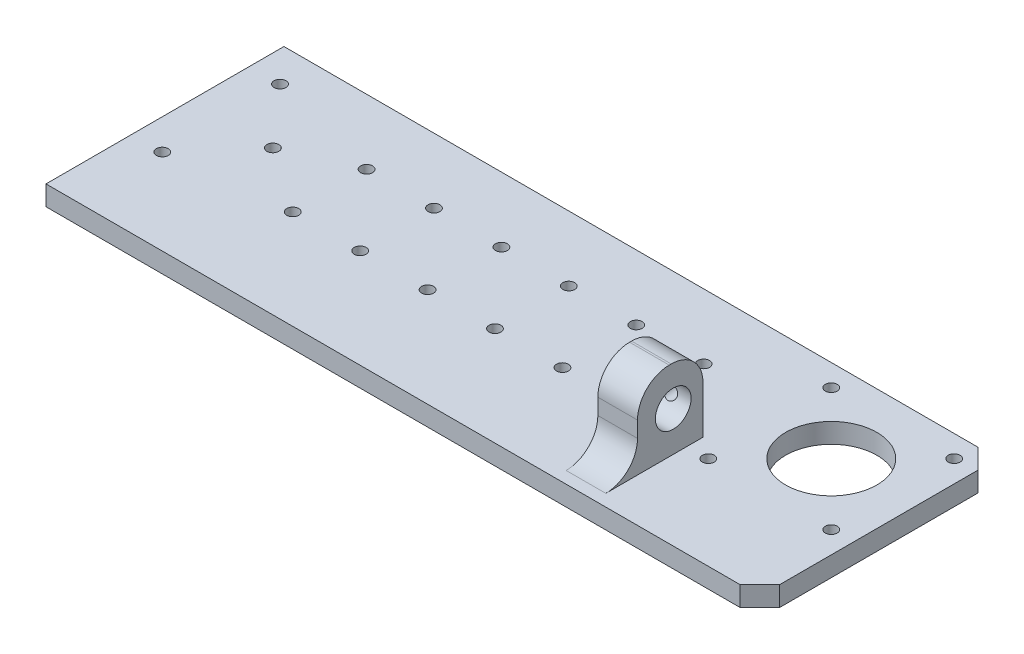
SolidWorks part; units mm, degrees
ref_plane "정면" through (0, 0, 0) normal (0, 0, 1) x (1, 0, 0)
ref_plane "윗면" through (0, 0, 0) normal (0, 1, 0) x (1, 0, 0)
ref_plane "우측면" through (0, 0, 0) normal (1, 0, 0) x (0, 0, -1)
sketch "스케치1" plane through (0, 0, 0) normal (0, 1, 0) x (1, 0, 0)
  line L0 (-53.3677, 28.2576) -> (-53.3677, -31.7424)
  line L1 (-53.3677, -31.7424) -> (126.6323, -31.7424)
  line L2 (126.6323, -31.7424) -> (126.6323, 28.2576)
  line L3 (126.6323, 28.2576) -> (-53.3677, 28.2576)
  circle A0 centre (105.6323, 7.2576) radius 11
  circle A2 centre (90.1323, 22.7576) radius 1.5
  circle A3 centre (121.1323, 22.7576) radius 1.5
  circle A4 centre (90.1323, -8.2424) radius 1.5
  circle A5 centre (121.1323, -8.2424) radius 1.5
  circle A6 centre (-32.6178, 4.7126) radius 1.5
  circle A7 centre (-45.6544, 19.5487) radius 1.5
  circle A8 centre (-45.6544, -10.1235) radius 1.5
  dimension "D4" = 31
  dimension "D1" = 180
  dimension "D3" = 60
  dimension "D5" = 31
extrude "보스-돌출3" add sketch "스케치1" along normal blind 5
sketch "스케치2" plane through (0, 5, 0) normal (0, 1, 0) x (1, 0, 0)
  line L2 (84.7825, 18.2576) -> (74.7825, 18.2576)
  line L3 (74.7825, 18.2576) -> (74.7825, -1.7424)
  line L4 (74.7825, -1.7424) -> (84.7825, -1.7424)
  line L5 (84.7825, -1.7424) -> (84.7825, 18.2576)
extrude "보스-돌출4" add sketch "스케치2" along normal blind 20
sketch "스케치4" plane through (74.7825, 0, 0) normal (-1, 0, 0) x (0, 0, 1)
  line L0 (1.7424, 25) -> (-8.2576, 25)
  line L1 (-18.2576, 25) -> (1.7424, 25) construction
  line L2 (-8.2576, 25) -> (-8.2576, 15)
  circle A0 centre (-8.2576, 15) radius 4
extrude "컷-돌출1" cut sketch "스케치4" against normal blind 20
sketch "스케치7" plane through (84.7825, 0, 0) normal (1, 0, 0) x (0, 0, -1)
  line L0 (18.2576, 25) -> (15.2576, 25)
  line L1 (-1.7424, 25) -> (18.2576, 25) construction
  line L2 (15.2576, 25) -> (15.2576, 5)
  line L3 (-1.7424, 5) -> (18.2576, 5) construction
  line L4 (15.2576, 5) -> (18.2576, 5)
  line L5 (18.2576, 5) -> (18.2576, 25)
  line L6 (-1.7424, 25) -> (1.2576, 25)
  line L7 (1.2576, 25) -> (1.2576, 5)
  line L8 (1.2576, 5) -> (-1.7424, 5)
  line L9 (-1.7424, 5) -> (-1.7424, 25)
  dimension "D1" = 3
  dimension "D2" = 3
sketch "스케치8" plane through (84.7825, 0, 0) normal (1, 0, 0) x (0, 0, -1)
  line L1 (15.2576, 25) -> (18.2576, 25)
  line L2 (15.2576, 25) -> (15.2576, 5)
  line L3 (15.2576, 5) -> (18.2576, 5)
  line L4 (18.2576, 25) -> (18.2576, 5)
  line L5 (1.2576, 25) -> (-1.7424, 25)
  line L6 (1.2576, 25) -> (1.2576, 5)
  line L7 (1.2576, 5) -> (-1.7424, 5)
  line L8 (-1.7424, 25) -> (-1.7424, 5)
extrude "컷-돌출4" cut sketch "스케치8" against normal blind 10
sketch "스케치9" plane through (84.7825, 0, 0) normal (1, 0, 0) x (0, 0, -1)
  line L0 (8.2576, 15) -> (1.7576, 15)
  line L1 (1.7576, 15) -> (1.7576, 5)
  line L2 (1.2576, 25) -> (15.2576, 25)
  line L3 (1.2576, 25) -> (1.2576, 5)
  line L4 (1.2576, 5) -> (15.2576, 5)
  line L5 (15.2576, 25) -> (15.2576, 5)
  line L6 (1.7576, 5) -> (1.7576, 25)
  line L8 (1.7576, 25) -> (-12.2424, 25)
  line L9 (1.7576, 25) -> (1.7576, 5)
  line L10 (1.7576, 5) -> (-12.2424, 5)
  line L11 (-12.2424, 25) -> (-12.2424, 5)
  circle A0 centre (-5.2424, 15) radius 4
  dimension "D3" = 8
  dimension "D1" = 14
  dimension "D2" = 6.5
  dimension "D4" = 7
sketch "스케치10" plane through (84.7825, 0, 0) normal (1, 0, 0) x (0, 0, -1)
  line L1 (-12.2424, 25) -> (1.7576, 25)
  line L2 (-12.2424, 25) -> (-12.2424, 5)
  line L3 (-12.2424, 5) -> (1.7576, 5)
  line L4 (1.7576, 25) -> (1.7576, 5)
extrude "보스-돌출5" add sketch "스케치10" against normal blind 10
extrude "컷-돌출5" cut sketch "스케치9" against normal blind 10 contours A0
sketch "스케치11" plane through (84.7825, 0, 0) normal (1, 0, 0) x (0, 0, -1)
  line L1 (-12.2424, 5) -> (15.2576, 5) construction
  line L3 (1.7576, 5) -> (15.2576, 5)
  line L4 (1.7576, 5) -> (1.7576, 25)
  line L5 (1.7576, 25) -> (15.2576, 25)
  line L6 (15.2576, 5) -> (15.2576, 25)
sketch "스케치12" plane through (84.7825, 0, 0) normal (1, 0, 0) x (0, 0, -1)
  line L1 (1.7576, 25) -> (15.2576, 25)
  line L2 (1.7576, 25) -> (1.7576, 5)
  line L3 (1.7576, 5) -> (15.2576, 5)
  line L4 (15.2576, 25) -> (15.2576, 5)
extrude "컷-돌출6" cut sketch "스케치12" against normal blind 10
sketch "스케치14" plane through (0, 5, 0) normal (0, 1, 0) x (1, 0, 0)
  line L0 (105.6323, 7.2576) -> (105.6323, 0.7576)
  line L1 (84.7825, 1.7576) -> (105.6323, 1.7576)
  dimension "D1" = 6.5
sketch "스케치15" plane through (84.7825, 0, 0) normal (1, 0, 0) x (0, 0, -1)
  line L0 (-12.2424, 5) -> (1.7576, 5) construction
  line L1 (1.7576, 25) -> (0.7576, 25)
  line L2 (1.7576, 25) -> (1.7576, 5)
  line L3 (1.7576, 5) -> (0.7576, 5)
  line L4 (0.7576, 25) -> (0.7576, 5)
  dimension "D1" = 1
extrude "컷-돌출7" cut sketch "스케치15" against normal blind 10
fillet "필렛5" radius 5 2 edges at (79.7825, 25, -0.7576) (79.7825, 25, 12.2424)
sketch "스케치16" plane through (0, 5, 0) normal (0, 1, 0) x (1, 0, 0)
  line L0 (105.6323, 7.2576) -> (105.6323, 0.7576)
sketch "스케치17" plane through (0, 5, 0) normal (0, 1, 0) x (1, 0, 0)
  line L0 (105.6323, 7.2576) -> (105.6323, -5.7424)
  line L1 (105.6323, -5.7424) -> (84.7825, -5.7424)
  line L2 (84.7825, -12.2424) -> (84.7825, 0.7576) construction
  line L3 (74.7825, 0.7576) -> (74.7825, -12.2424) construction
  line L4 (84.7825, -5.7424) -> (74.7825, -5.7424)
  line L5 (84.7825, -5.7424) -> (84.7825, 3.2576)
  line L6 (84.7825, 3.2576) -> (74.7825, 3.2576)
  line L7 (74.7825, -5.7424) -> (74.7825, 3.2576)
  line L9 (84.7825, -5.7424) -> (74.7825, -5.7424)
  line L10 (84.7825, -5.7424) -> (84.7825, -14.7424)
  line L11 (84.7825, -14.7424) -> (74.7825, -14.7424)
  line L12 (74.7825, -5.7424) -> (74.7825, -14.7424)
  dimension "D1" = 9
  dimension "D2" = 9
sketch "스케치20" plane through (74.7825, 0, 0) normal (-1, 0, 0) x (0, 0, 1)
  line L1 (-3.2576, 5) -> (-1.0985, 5)
  line L2 (-3.2576, 5) -> (-3.2576, 27.106)
  line L3 (-3.2576, 27.106) -> (-1.0985, 27.106)
  line L4 (-1.0985, 5) -> (-1.0985, 27.106)
sketch "스케치21" plane through (0, 5, 0) normal (0, 1, 0) x (1, 0, 0)
  line L1 (84.7825, -14.7424) -> (74.7825, -14.7424)
  line L2 (84.7825, -14.7424) -> (84.7825, 3.2576)
  line L3 (84.7825, 3.2576) -> (74.7825, 3.2576)
  line L4 (74.7825, -14.7424) -> (74.7825, 3.2576)
extrude "보스-돌출6" add sketch "스케치21" along normal blind 20
sketch "스케치23" plane through (84.7825, 0, 0) normal (1, 0, 0) x (0, 0, -1)
  line L1 (-14.7424, 25) -> (3.2576, 25) construction
  circle A0 centre (-5.7424, 15) radius 4
  dimension "D1" = 10
sketch "스케치24" plane through (0, 5, 0) normal (0, 1, 0) x (1, 0, 0)
  line L0 (105.6323, 7.2576) -> (105.6323, 0.7576)
sketch "스케치25" plane through (0, 5, 0) normal (0, 1, 0) x (1, 0, 0)
  line L1 (84.7825, 3.2576) -> (73.4713, 3.2576)
  line L2 (84.7825, 3.2576) -> (84.7825, 1.7576)
  line L3 (84.7825, 1.7576) -> (73.4713, 1.7576)
  line L4 (73.4713, 3.2576) -> (73.4713, 1.7576)
extrude "컷-돌출10" cut sketch "스케치25" along normal blind 20
sketch "스케치28" plane through (0, 5, 0) normal (0, 1, 0) x (1, 0, 0)
  line L1 (84.7825, 1.7576) -> (74.7825, 1.7576)
  line L2 (84.7825, 1.7576) -> (84.7825, -14.7424)
  line L3 (84.7825, -14.7424) -> (74.7825, -14.7424)
  line L4 (74.7825, 1.7576) -> (74.7825, -14.7424)
sketch "스케치31" plane through (0, 5, 0) normal (0, 1, 0) x (1, 0, 0)
  line L0 (105.6323, 7.2576) -> (105.6323, 0.7576)
sketch "스케치34" plane through (0, 0, 14.7424) normal (0, 0, 1) x (1, 0, 0)
  line L1 (74.7825, 25) -> (84.7825, 25)
  line L2 (74.7825, 25) -> (74.7825, 5)
  line L3 (74.7825, 5) -> (84.7825, 5)
  line L4 (84.7825, 25) -> (84.7825, 5)
sketch "스케치36" plane through (84.7825, 0, 0) normal (1, 0, 0) x (0, 0, -1)
  line L0 (1.7576, 25) -> (-5.7424, 25)
  line L1 (-14.7424, 25) -> (1.7576, 25) construction
  line L6 (1.7576, 5) -> (1.7576, 25)
  line L7 (1.7576, 25) -> (-14.7424, 25)
  line L8 (-14.7424, 25) -> (-14.7424, 5)
  line L9 (-14.7424, 5) -> (1.7576, 5)
  line L11 (1.7576, 25) -> (-5.7424, 25)
  dimension "D1" = 0
sketch "스케치37" plane through (0, 0, 14.7424) normal (0, 0, 1) x (1, 0, 0)
  line L1 (84.7825, 25) -> (74.7825, 25)
  line L2 (84.7825, 25) -> (84.7825, 5)
  line L3 (84.7825, 5) -> (74.7825, 5)
  line L4 (74.7825, 25) -> (74.7825, 5)
extrude "보스-돌출9" add sketch "스케치37" along normal blind 6
sketch "스케치38" plane through (0, 0, -1.7576) normal (0, 0, -1) x (-1, 0, 0)
  line L1 (-74.7825, 25) -> (-84.7825, 25)
  line L2 (-74.7825, 25) -> (-74.7825, 5)
  line L3 (-74.7825, 5) -> (-84.7825, 5)
  line L4 (-84.7825, 25) -> (-84.7825, 5)
extrude "컷-돌출12" cut sketch "스케치38" against normal blind 6
sketch "스케치39" plane through (84.7825, 0, 0) normal (1, 0, 0) x (0, 0, -1)
  line L0 (-4.2424, 25) -> (-4.2424, 5) construction
  circle A0 centre (-11.7424, 15) radius 4
  dimension "D1" = 7.5
extrude "컷-돌출13" cut sketch "스케치39" against normal through all
fillet "필렛10" radius 8 3 edges at (79.7825, 25, 20.7424) (79.7825, 5, 20.7424) (79.7825, 25, 4.2424)
sketch "스케치41" plane through (0, 5, 0) normal (0, 1, 0) x (1, 0, 0)
  circle A0 centre (-16.1455, -6.7512) radius 1.5
  circle A1 centre (-16.1455, 11.8644) radius 1.5
  circle A2 centre (0.8545, 11.8644) radius 1.5
  circle A3 centre (0.8545, -6.7512) radius 1.5
  circle A4 centre (17.8545, 11.8644) radius 1.5
  circle A5 centre (17.8545, -6.7512) radius 1.5
  circle A6 centre (34.8545, 11.8644) radius 1.5
  circle A7 centre (34.8545, -6.7512) radius 1.5
  circle A8 centre (51.8545, 11.8644) radius 1.5
  circle A9 centre (51.8545, -6.7512) radius 1.5
  circle A10 centre (68.8545, 11.8644) radius 1.5
  circle A11 centre (68.8545, -6.7512) radius 1.5
  dimension "D1" = 6
extrude "컷-돌출14" cut sketch "스케치41" against normal blind 10
sketch "스케치42" plane through (0, 5, 0) normal (0, 1, 0) x (1, 0, 0)
  circle A0 centre (105.6323, 7.2576) radius 11.5
extrude "컷-돌출15" cut sketch "스케치42" against normal blind 10
sketch "스케치43" plane through (0, 0, 4.2424) normal (0, 0, -1) x (-1, 0, 0)
  line L0 (-84.7825, 17) -> (-84.7825, 5) construction
  circle A0 centre (-79.7825, 14.1217) radius 1.692
  dimension "D1" = 5
extrude "컷-돌출16" cut sketch "스케치43" against normal blind 10
sketch "스케치44" plane through (74.7825, 0, 0) normal (-1, 0, 0) x (0, 0, 1)
  circle A0 centre (11.7424, 15) radius 4.5
extrude "컷-돌출17" cut sketch "스케치44" against normal blind 10
sketch "스케치45" plane through (0, 5, 0) normal (0, 1, 0) x (1, 0, 0)
  line L1 (-45.6544, 19.5487) -> (66.3456, 19.5487)
  line L2 (-45.6544, 19.5487) -> (-45.6544, -25.4513)
  line L3 (-45.6544, -25.4513) -> (66.3456, -25.4513)
  line L4 (66.3456, 19.5487) -> (66.3456, -25.4513)
  line L5 (-41.6544, 15.5487) -> (62.3456, 15.5487)
  line L6 (-41.6544, 15.5487) -> (-41.6544, -21.4513)
  line L7 (-41.6544, -21.4513) -> (62.3456, -21.4513)
  line L8 (62.3456, 15.5487) -> (62.3456, -21.4513)
  dimension "D1" = 45
  dimension "D2" = 112
  dimension "D3" = 4
  dimension "D4" = 4
  dimension "D5" = 4
  dimension "D6" = 4
sketch "스케치46" plane through (0, 5, 0) normal (0, 1, 0) x (1, 0, 0)
  line L0 (126.6323, 28.2576) -> (121.6323, 28.2576)
  line L1 (126.6323, 28.2576) -> (-53.3677, 28.2576) construction
  line L2 (121.6323, 28.2576) -> (126.6323, 23.2576)
  line L3 (126.6323, -31.7424) -> (126.6323, 28.2576) construction
  line L4 (126.6323, 23.2576) -> (126.6323, 28.2576)
  line L5 (126.6323, -31.7424) -> (121.6323, -31.7424)
  line L6 (-53.3677, -31.7424) -> (126.6323, -31.7424) construction
  line L7 (121.6323, -31.7424) -> (126.6323, -26.7424)
  line L8 (126.6323, -26.7424) -> (126.6323, -31.7424)
extrude "컷-돌출18" cut sketch "스케치46" against normal blind 10
